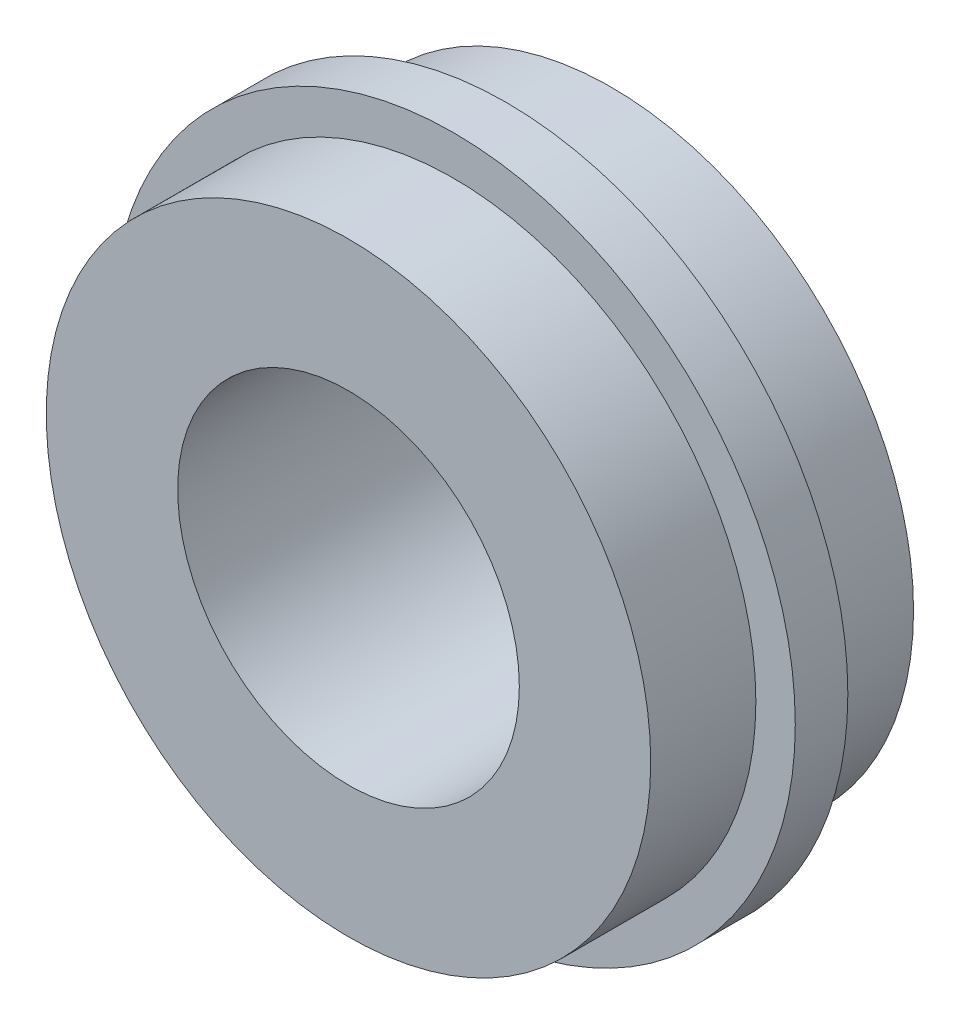
SolidWorks part; units mm, degrees
ref_plane "前视基准面" through (0, 0, 0) normal (0, 0, 1) x (1, 0, 0)
ref_plane "上视基准面" through (0, 0, 0) normal (0, 1, 0) x (1, 0, 0)
ref_plane "右视基准面" through (0, 0, 0) normal (1, 0, 0) x (0, 0, -1)
sketch "草图1" plane through (0, 0, 0) normal (0, 1, 0) x (1, 0, 0)
  line L0 (0, 0) -> (0, 88.5202) construction
  line L1 (0, 0) -> (130.9696, 0) construction
  line L2 (11.5, 5) -> (11.5, 1)
  line L3 (6.5, 5) -> (11.5, 5)
  line L4 (6.5, 5) -> (6.5, -5)
  line L5 (6.5, -5) -> (11.5, -5)
  line L6 (13, 1) -> (13, -1)
  line L7 (11.5, 1) -> (13, 1)
  line L8 (11.5, -1) -> (13, -1)
  line L9 (11.5, -5) -> (11.5, -1)
  dimension "D1" = 6.5
  dimension "D2" = 10
  dimension "D3" = 13
  dimension "D4" = 5
  dimension "D5" = 2
revolve "旋转1" add sketch "草图1" angle 360 about L0
